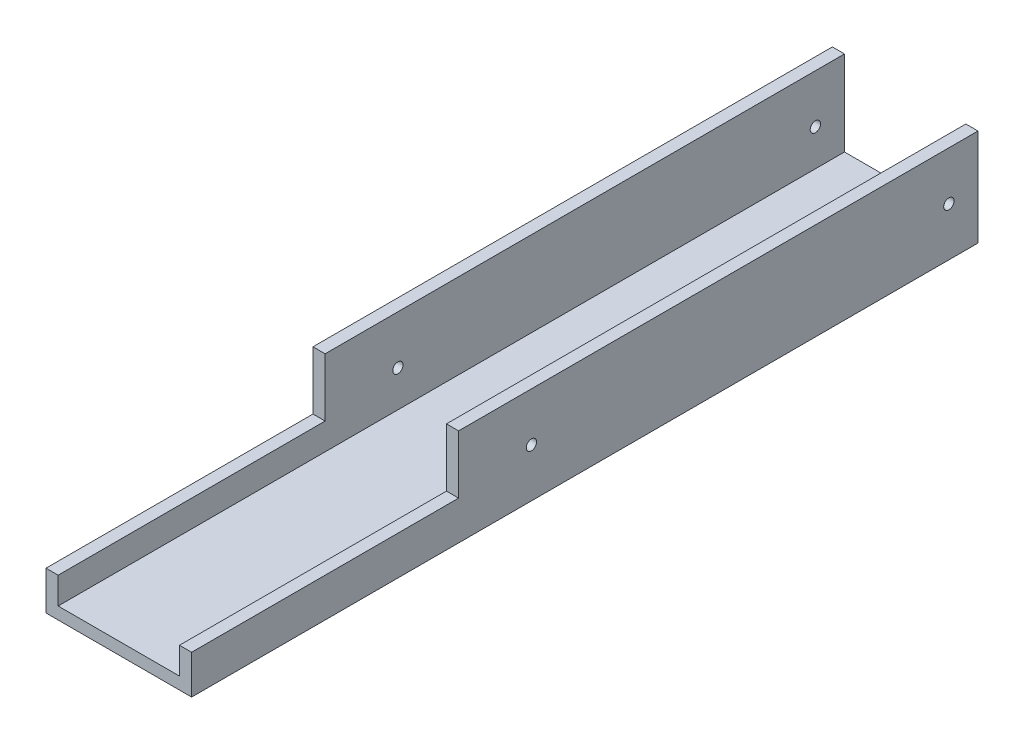
SolidWorks part; units mm, degrees
other "Markup1"
sketch "Sketch4" plane through (19.05, 12.7, 609.6) normal (0.165, 0.2552, 0.9527) x (0.9626, 0.1685, -0.2119)
ref_plane "Front" through (0, 0, 0) normal (0, 0, 1) x (1, 0, 0)
ref_plane "Top" through (0, 0, 0) normal (0, 1, 0) x (1, 0, 0)
ref_plane "Right" through (0, 0, 0) normal (1, 0, 0) x (0, 0, -1)
sketch "Sketch1" plane through (0, 0, 0) normal (0, 0, 1) x (1, 0, 0)
  line L0 (0, -12.7) -> (0, 12.7) construction
  line L1 (-19.05, 0) -> (19.05, 0) construction
  line L2 (15.875, 12.7) -> (-15.875, 12.7) construction
  line L3 (-19.05, -12.7) -> (19.05, -12.7)
  line L4 (-19.05, -12.7) -> (-19.05, 12.7)
  line L5 (-19.05, 12.7) -> (19.05, 12.7)
  line L6 (19.05, -12.7) -> (19.05, 12.7)
  line L7 (-19.05, -12.7) -> (19.05, 12.7) construction
  line L8 (-19.05, 12.7) -> (19.05, -12.7) construction
  line L9 (-15.875, -12.7) -> (15.875, -12.7)
  point P3 (0, 0)
  point P4 (0, 0)
  point P8 (0, 0)
  point P13 (19.05, -9.525)
  point P17 (0, 12.7)
  point P20 (0, -12.7)
  dimension "Outside Width" = 38.1
  dimension "Outside Height" = 25.4
  dimension "Inside Height" = 22.225
  dimension "Wall Thickness" = 3.175
  dimension "Inside Width" = 31.75
sketch "Sketch2" plane through (0, 0, 0) normal (1, 0, 0) x (0, 0, -1)
  line L0 (-609.6, 0) -> (609.6, 0) construction
  dimension "Length" = 1219.2
sketch "Sketch3" plane through (0, 0, 0) normal (0, 0, 1) x (1, 0, 0)
  line L0 (-19.05, 12.7) -> (-19.05, -12.7)
  line L1 (-19.05, -12.7) -> (19.05, -12.7)
  line L2 (19.05, -12.7) -> (19.05, 12.7)
  line L3 (19.05, 12.7) -> (15.875, 12.7)
  line L4 (15.875, 12.7) -> (15.875, -9.525)
  line L5 (15.875, -9.525) -> (-15.875, -9.525)
  line L6 (-15.875, -9.525) -> (-15.875, 12.7)
  line L7 (-15.875, 12.7) -> (-19.05, 12.7)
  line L8 (-15.875, -9.525) -> (-15.875, -12.7) construction
  dimension "D1" = 25.4
  dimension "D2" = 38.1
  dimension "D3" = 3.175
extrude "Boss-Extrude2" add sketch "Sketch3" along normal mid plane 1219.2
sketch "Reference Sketch1" plane through (0, 0, 0) normal (1, 0, 0) x (0, 0, -1)
  line L0 (-609.6, 0) -> (609.6, 0) construction
  point P0 (-565.15, 0)
  point P1 (565.15, 0)
  dimension "D1" = 44.45
  dimension "D2" = 44.45
sketch "Sketch5" plane through (0, 0, 609.6) normal (0, 0, 1) x (1, 0, 0)
  line L0 (-19.05, 12.7) -> (-15.875, 12.7)
  line L1 (-15.875, 12.7) -> (-15.875, -9.525)
  line L2 (-15.875, -9.525) -> (15.875, -9.525)
  line L3 (15.875, -9.525) -> (15.875, 12.7)
  line L4 (19.05, 12.7) -> (15.875, 12.7) construction
  line L5 (15.875, 12.7) -> (15.875, -9.525) construction
  line L6 (15.875, 12.7) -> (19.05, 12.7)
  line L7 (19.05, 12.7) -> (19.05, -12.7)
  line L8 (19.05, -12.7) -> (-19.05, -12.7)
  line L9 (-19.05, -12.7) -> (-19.05, 12.7)
extrude "Cut-Extrude1" cut sketch "Sketch5" against normal blind 1013.46
sketch "Sketch7" plane through (-19.05, 0, 0) normal (-1, 0, 0) x (0, 0, 1)
  line L0 (-609.6, 12.7) -> (-609.6, -12.7) construction
  line L1 (-403.86, 12.7) -> (-609.6, 12.7) construction
  line L2 (-403.86, -12.7) -> (-609.6, -12.7) construction
  point P0 (-601.98, 0)
  dimension "D1" = 7.62
  dimension "D2" = 12.7
hole_wizard "#6-32 Tapped Hole1" positions "Sketch7" profile "Sketch8" tap size "#6-32" standard "ANSI Inch" end condition through all
cosmetic thread "Hole Thread1" parameters "D2"=3.5052
sketch "Sketch8" plane through (-19.05, 0, -601.98) normal (0, 1, 0) x (0, 0, 1)
  line L0 (0, 0) -> (0, 38.1)
  line L1 (0, 38.1) -> (1.3525, 38.1)
  line L2 (1.3525, 38.1) -> (1.3525, 0)
  line L5 (1.3525, 0) -> (0, 0)
  line L11 (0, -6.35) -> (0, 107.95) construction
  dimension "Thru Tap Drill Dia." = 2.7051
  dimension "Thru Tap Drill Depth" = 38.1
sketch "Sketch9" plane through (-19.05, 0, 0) normal (-1, 0, 0) x (0, 0, 1)
  line L1 (-403.86, -12.7) -> (-609.6, -12.7) construction
  line L2 (-609.6, 12.7) -> (-609.6, -12.7) construction
  point P0 (-492.76, 0)
  dimension "D1" = 116.84
  dimension "D2" = 12.7
hole_wizard "#6-32 Tapped Hole2" positions "Sketch9" profile "Sketch10" tap size "#6-32" standard "ANSI Inch" end condition through all
sketch "Sketch10" plane through (-19.05, 0, -492.76) normal (0, 1, 0) x (0, 0, 1)
  line L0 (0, 0) -> (0, 38.1)
  line L1 (0, 38.1) -> (1.3525, 38.1)
  line L2 (1.3525, 38.1) -> (1.3525, 0)
  line L5 (1.3525, 0) -> (0, 0)
  line L11 (0, -6.35) -> (0, 107.95) construction
  dimension "Thru Tap Drill Dia." = 2.7051
  dimension "Thru Tap Drill Depth" = 38.1
cosmetic thread "Hole Thread2" parameters "D2"=3.5052
sketch "Sketch13" plane through (-19.05, 0, 0) normal (-1, 0, 0) x (0, 0, 1)
  line L1 (-403.86, 12.7) -> (-473.71, 12.7)
  line L2 (-403.86, 12.7) -> (-403.86, -2.54)
  line L3 (-403.86, -2.54) -> (-473.71, -2.54)
  line L4 (-473.71, 12.7) -> (-473.71, -2.54)
  dimension "D1" = 69.85
  dimension "D2" = 15.24
extrude "Cut-Extrude4" cut sketch "Sketch13" against normal through all both and the other way through all
equation "\"D1@Sketch3\" = \"Outside Height@Sketch1\""
equation "\"D2@Sketch3\" = \"Outside Width@Sketch1\""
equation "\"D3@Sketch3\" = \"Wall Thickness@Sketch1\""
equation "\"D1@Reference Sketch1\"=\"Outside Height@Sketch1\" * 1.75"
equation "\"D2@Reference Sketch1\" = \"D1@Reference Sketch1\""
equation "\"D1@Boss-Extrude2\" = \"Length@Sketch2\""
equation "\"Inside Height@Sketch1\"=\"Outside Height@Sketch1\"-\"Wall Thickness@Sketch1\""
equation "\"Inside Width@Sketch1\"=\"Outside Width@Sketch1\"-\"Wall Thickness@Sketch1\"*2"
